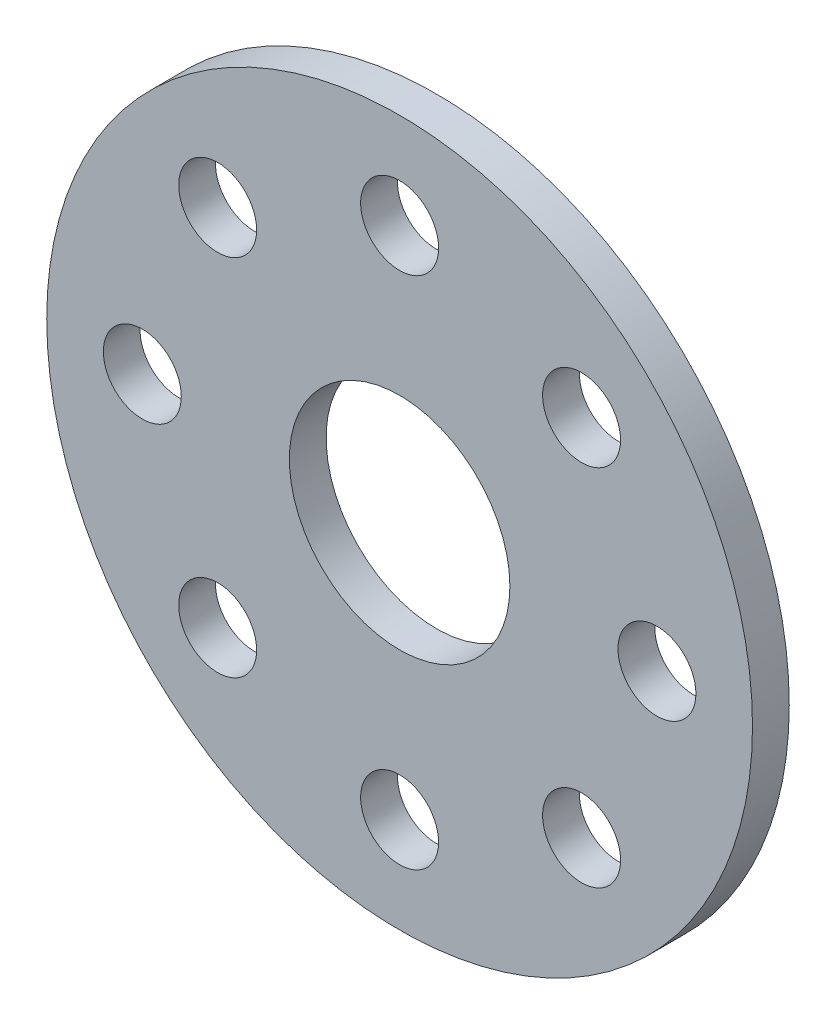
SolidWorks part; units mm, degrees
ref_plane "Front" through (0, 0, 0) normal (0, 0, 1) x (1, 0, 0)
ref_plane "Top" through (0, 0, 0) normal (0, 1, 0) x (1, 0, 0)
ref_plane "Right" through (0, 0, 0) normal (1, 0, 0) x (0, 0, -1)
sketch "Sketch1" plane through (0, 0, 0) normal (0, 0, 1) x (1, 0, 0)
  circle A0 centre (0, 0) radius 24
  circle A1 centre (0, 0) radius 7.5
  dimension "D1" = 48
  dimension "D2" = 15
extrude "Boss-Extrude1" add sketch "Sketch1" along normal mid plane 2.5
hole_wizard "M5 Clearance Hole1" positions "Sketch2" profile "Sketch3" hole size "M5" standard "ANSI Metric" end condition up to next
sketch "Sketch2" plane through (0, 0, 1.25) normal (0, 0, 1) x (1, 0, 0)
  circle A0 centre (0, 0) radius 17.5
  point P0 (0, -17.5)
  point P12 (-12.3744, -12.3744)
  point P13 (-17.5, 0)
  point P14 (-12.3744, 12.3744)
  point P15 (0, 17.5)
  point P16 (12.3744, 12.3744)
  point P17 (17.5, 0)
  point P18 (12.3744, -12.3744)
  dimension "D1" = 35
  dimension "D2" = 8
sketch "Sketch3" plane through (0, -17.5, 1.25) normal (1, 0, 0) x (0, -1, 0)
  line L0 (0, 0) -> (0, 2.5)
  line L1 (0, 2.5) -> (2.65, 2.5)
  line L2 (2.65, 2.5) -> (2.65, 0)
  line L5 (2.65, 0) -> (0, 0)
  line L11 (0, -6.35) -> (0, 107.95) construction
  dimension "Thru Hole Dia." = 5.3
  dimension "Thru Hole Depth" = 2.5
